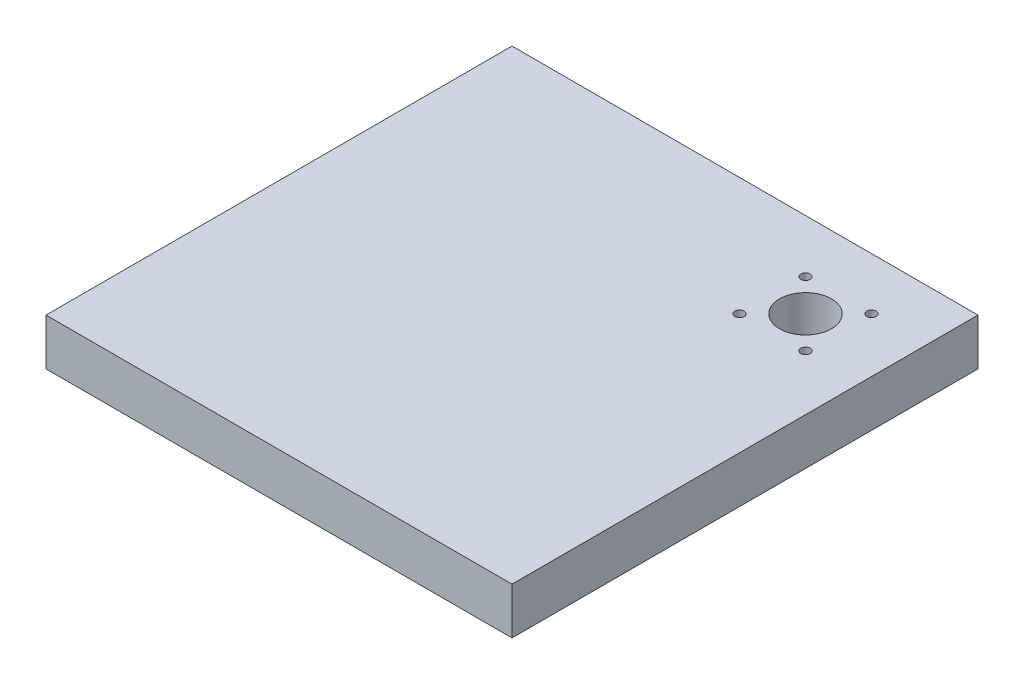
SolidWorks part; units mm, degrees
ref_plane "Front" through (0, 0, 0) normal (0, 0, 1) x (1, 0, 0)
ref_plane "Top" through (0, 0, 0) normal (0, 1, 0) x (1, 0, 0)
ref_plane "Right" through (0, 0, 0) normal (1, 0, 0) x (0, 0, -1)
sketch "Sketch1" plane through (0, 0, 0) normal (0, 1, 0) x (1, 0, 0)
  line L1 (-127, 127) -> (127, 127)
  line L2 (-127, 127) -> (-127, -127)
  line L3 (-127, -127) -> (127, -127)
  line L4 (127, 127) -> (127, -127)
  line L5 (-127, 127) -> (127, -127) construction
  line L6 (-127, -127) -> (127, 127) construction
  point P0 (0, 0)
  dimension "D1" = 254
  dimension "D2" = 254
extrude "Boss-Extrude1" add sketch "Sketch1" along normal blind 25.4
hole_wizard "#10 Clearance Hole1" positions "Sketch2" profile "Sketch4" hole size "#10" standard "ANSI Inch" end condition up to next
sketch "Sketch2" plane through (0, 0, 0) normal (0, -1, 0) x (-1, 0, 0)
  arc A1 (-63.4338, 62.6395) -> (-59.3952, 62.6395) centre (-61.4145, 62.6395) ccw construction
  point P0 (-61.4145, 62.6395)
  point P11 (-97.3355, 98.5605)
  point P14 (-61.875, 98.1)
  point P17 (-96.875, 63.1)
sketch "Sketch4" plane through (61.4145, 0, -62.6395) normal (1, 0, 0) x (0, 0, -1)
  line L0 (0, 0) -> (0, 25.4)
  line L1 (0, 25.4) -> (2.5527, 25.4)
  line L2 (2.5527, 25.4) -> (2.5527, 0)
  line L5 (2.5527, 0) -> (0, 0)
  line L11 (0, -6.35) -> (0, 107.95) construction
  dimension "Thru Hole Dia." = 5.1054
  dimension "Thru Hole Depth" = 25.4
hole_wizard "1 (1.115) Dowel Hole1" positions "Sketch5" profile "Sketch6" hole size "1" standard "ANSI Inch" end condition through all
sketch "Sketch5" plane through (0, 0, 0) normal (0, -1, 0) x (-1, 0, 0)
  point P0 (-79.375, 80.6)
sketch "Sketch6" plane through (79.375, 0, -80.6) normal (1, 0, 0) x (0, 0, -1)
  line L0 (0, 0) -> (0, 25.4)
  line L1 (0, 25.4) -> (14.1605, 25.4)
  line L2 (14.1605, 25.4) -> (14.1605, 0)
  line L5 (14.1605, 0) -> (0, 0)
  line L11 (0, -6.35) -> (0, 107.95) construction
  dimension "Thru Hole Dia." = 28.321
  dimension "Thru Hole Depth" = 25.4
